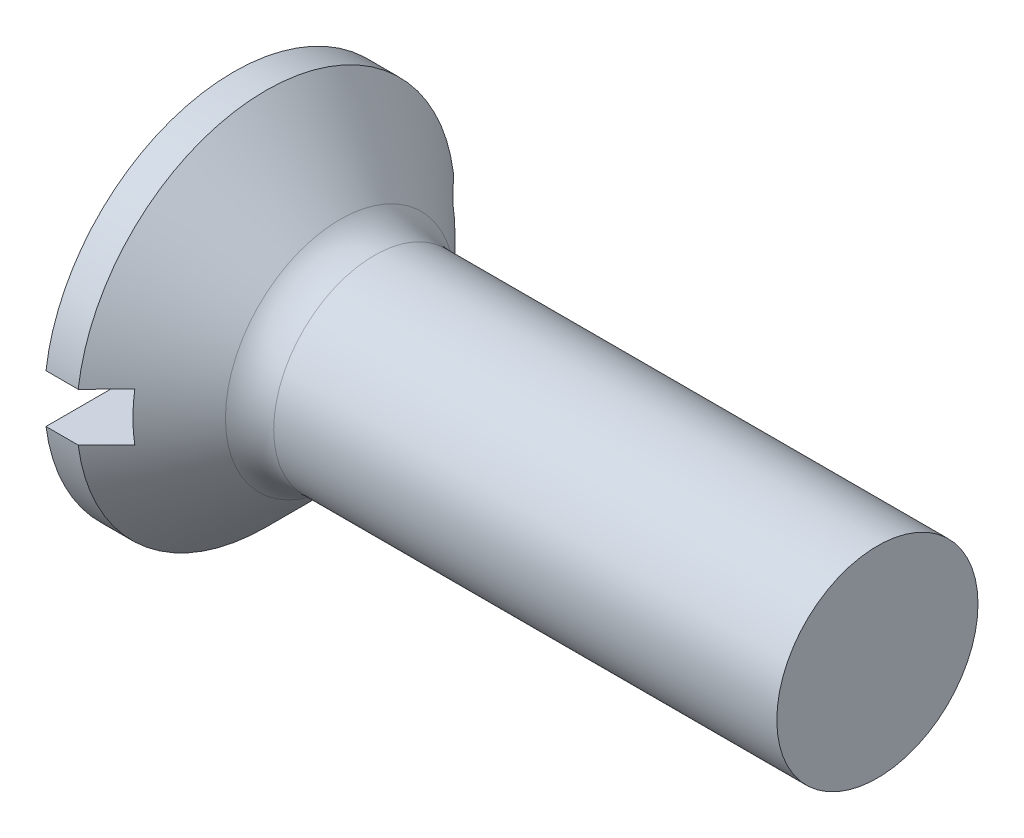
SolidWorks part; units mm, degrees
revolve "Base-Revolve" add sketch "BodySke" angle 360 about L5
sketch "BodySke" plane through (0, 0, 0) normal (0, 0, 1) x (1, 0, 0)
  line L0 (0, 0) -> (0, 2.35)
  line L1 (0, 2.35) -> (0.4, 2.35)
  line L2 (1.5, 1.25) -> (8, 1.25)
  line L3 (8, 1.25) -> (8, 0)
  line L4 (8, 0) -> (0, 0)
  line L5 (-6.35, 0) -> (82.55, 0) construction
  line L6 (1.5, -1.25) -> (8, -1.25) construction
  line L7 (0.4, -2.35) -> (1.5, -1.25) construction
  line L8 (0.4, 2.35) -> (1.5, 1.25)
  line L9 (0, -2.35) -> (0.4, -2.35) construction
  line L10 (1.95, 2.8375) -> (1.95, -6.6875) construction
  line L11 (0, 6.35) -> (0, -3.175) construction
  dimension "Diameter" = 2.5
  dimension "Length" = 8
  dimension "Head_ht" = 1.5
  dimension "Head_dia" = 4.7
  dimension "Head_ang" = 90
  dimension "D6" = 0.4
  dimension "Advance" = 0.45
  dimension "Thread_nom" = 8
cosmetic thread "ThreadCosmetic" [suppressed] parameters "Thread_length"=6.05, "Thread_minor"=1.993
extrude "Slot" cut sketch "Sketch2" against normal blind 0.75
sketch "Sketch2" plane through (0, 0, 0) normal (-1, 0, 0) x (0, 0, 1)
  line L0 (-2.35, -0.3) -> (2.35, -0.3)
  line L1 (-2.35, -0.3) -> (-2.35, 0.3)
  line L2 (2.35, 0.3) -> (-2.35, 0.3)
  line L3 (2.35, 0.3) -> (2.35, -0.3)
  dimension "Slot_width" = 0.6
  dimension "D1" = 0.3
  dimension "D2" = 4.7
  dimension "D3" = 2.35
ref_plane "Plane1" through (0, 0, 0) normal (0, 0, 1) x (1, 0, 0)
ref_plane "Plane2" through (0, 0, 0) normal (0, 1, 0) x (1, 0, 0)
ref_plane "Plane3" through (0, 0, 0) normal (1, 0, 0) x (0, 0, -1)
fillet "Fillet1" radius 0.6 1 edges at (1.5, 0, 1.25)
sketch "ThdSchSke" plane through (0, 0, 0) normal (0, 0, 1) x (1, 0, 0)
  line L0 (1.95, -0.9965) -> (1.7725, -1.25)
  line L1 (1.95, -0.9965) -> (2.1275, -1.25)
  line L2 (2.1275, -1.25) -> (2.1275, -1.5625)
  line L3 (-3.175, 0) -> (5.1513, 0) construction
  line L5 (2.1275, -1.5625) -> (1.7725, -1.5625)
  line L6 (1.7725, -1.5625) -> (1.7725, -1.25)
  line L7 (0, 2.35) -> (0, 0.3) construction
  dimension "Diameter" = 2.5
  dimension "Thread_minor" = 1.993
  dimension "Start" = 1.95
revolve "ThreadSchematic" [suppressed] cut sketch "ThdSchSke" angle 360 about L3
pattern_linear "ThdSchPat" [suppressed]
equation "\"D1@Sketch2\" = \"Slot_width@Sketch2\" / 2"
equation "\"D2@Sketch2\" = \"Head_dia@BodySke\""
equation "\"D3@Sketch2\" = \"D2@Sketch2\" / 2"
equation "\"Thread_length@ThreadCosmetic\" = ((sgn( (\"Length@BodySke\" - \"Advance@BodySke\" * 1.0 - \"Head_ht@BodySke\" ) - \"Thread_nom@BodySke\" )-1)*( (\"Length@BodySke\" - \"Advance@BodySke\" * 1.0 - \"Head_ht@BodySke\" ) - \"Thread_nom@BodySke\" ))/-2+ \"Thread_nom@BodySke\""
equation "\"Thread_minor@ThdSchSke\" = \"Thread_minor@ThreadCosmetic\""
equation "\"Diameter@ThdSchSke\" = \"Diameter@BodySke\""
equation "\"Overcut@ThdSchSke\" = \"Diameter@BodySke\" * 1.25"
equation "\"Start@ThdSchSke\" = 0.000001 + \"Length@BodySke\" - \"Thread_length@ThreadCosmetic\"  '---Countersunk---"
equation "\"Num_threads@ThdSchPat\" = int( \"Thread_length@ThreadCosmetic\" / \"Advance@BodySke\" + 0.999 )  + 1"
equation "\"Advance@ThdSchPat\" = \"Thread_length@ThreadCosmetic\" /  (\"Num_threads@ThdSchPat\" - 1) 'relax it"
